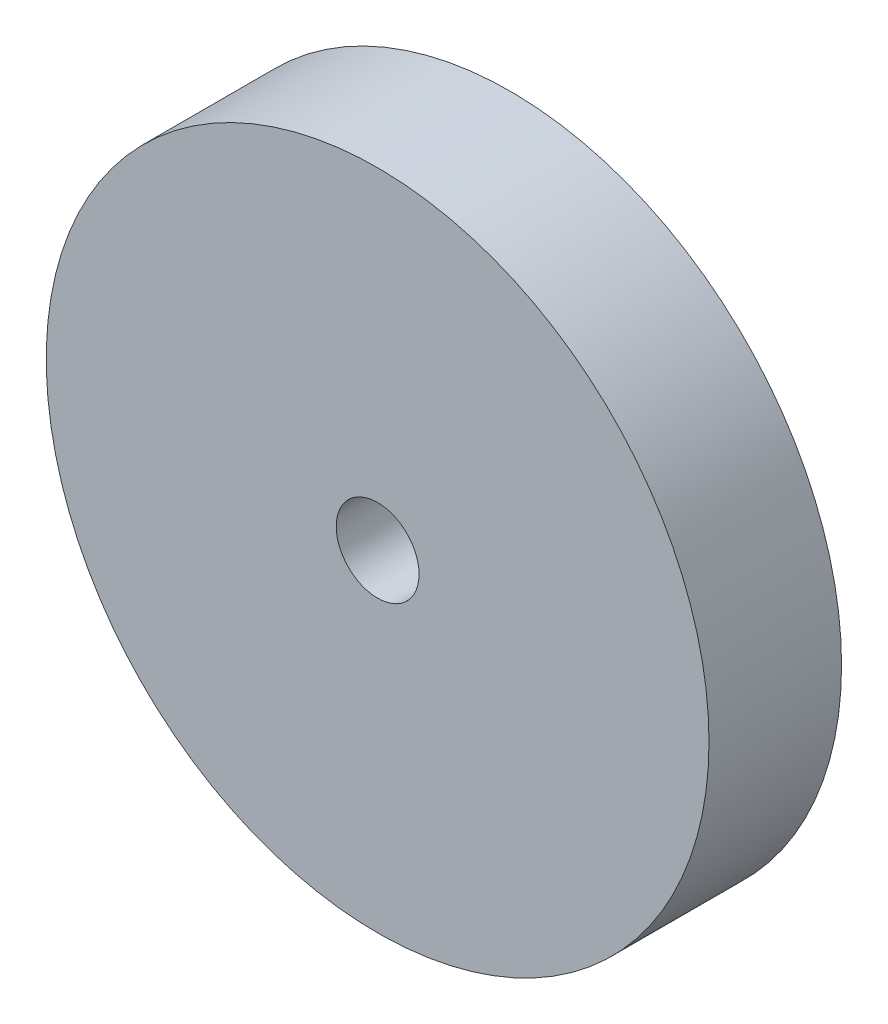
SolidWorks part; units mm, degrees
material "自訂玻璃纖維"
ref_plane "前基準面" through (0, 0, 0) normal (0, 0, 1) x (1, 0, 0)
ref_plane "上基準面" through (0, 0, 0) normal (0, 1, 0) x (1, 0, 0)
ref_plane "右基準面" through (0, 0, 0) normal (1, 0, 0) x (0, 0, -1)
sketch "草圖1" plane through (0, 0, 0) normal (0, 0, 1) x (1, 0, 0)
  circle A0 centre (-13.0879, 3.3421) radius 10
  circle A1 centre (-13.0879, 3.3421) radius 1.25
  point P14 (-13.0879, 3.3421)
  dimension "D1" = 20
  dimension "D2" = 2.5
extrude "填料-伸長1" add sketch "草圖1" along normal blind 4
